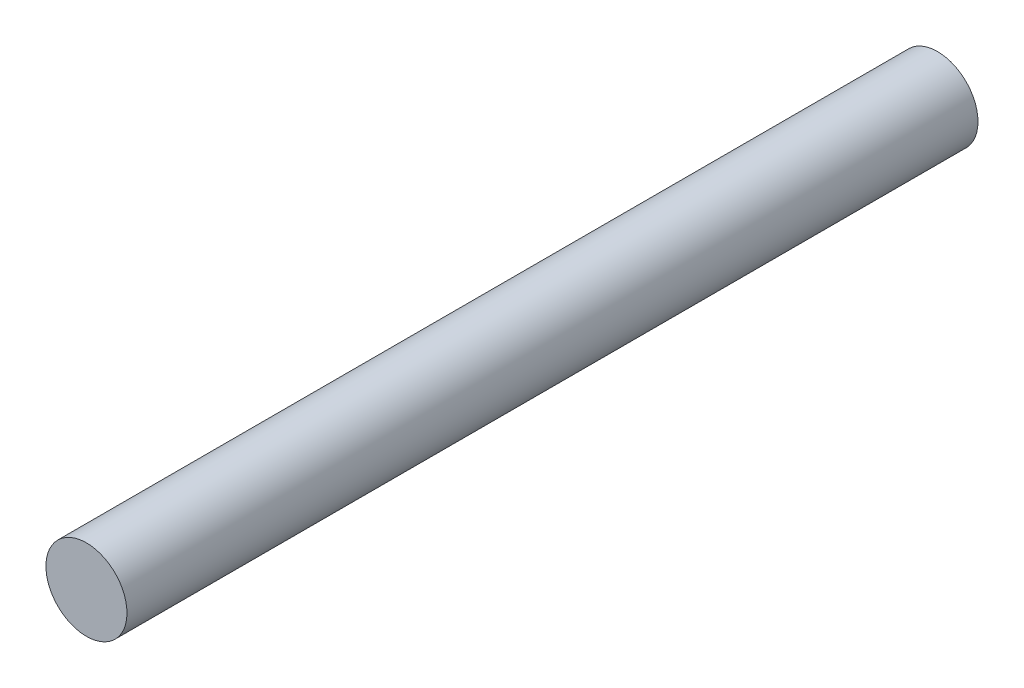
SolidWorks part; units mm, degrees
ref_plane "Front" through (0, 0, 0) normal (0, 0, 1) x (1, 0, 0)
ref_plane "Top" through (0, 0, 0) normal (0, 1, 0) x (1, 0, 0)
ref_plane "Right" through (0, 0, 0) normal (1, 0, 0) x (0, 0, -1)
sketch "Sketch1" plane through (0, 0, 0) normal (0, 0, 1) x (1, 0, 0)
  circle A0 centre (0, 0) radius 2.54
  dimension "D1" = 5.08
extrude "Boss-Extrude1" add sketch "Sketch1" along normal blind 53.34
sketch "Sketch2" plane through (0, 0, 53.34) normal (0, 0, 1) x (1, 0, 0)
  circle A0 centre (0, 0) radius 0.4445
  dimension "D1" = 0.889
